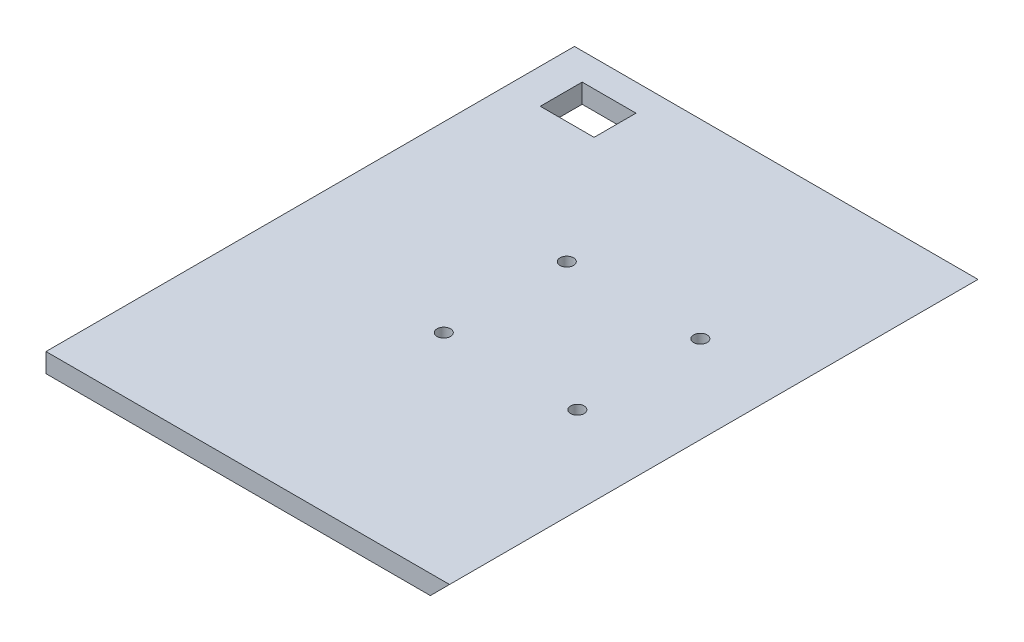
SolidWorks part; units mm, degrees
ref_plane "Ön Düzlem" through (0, 0, 0) normal (0, 0, 1) x (1, 0, 0)
ref_plane "Üst Düzlem" through (0, 0, 0) normal (0, 1, 0) x (1, 0, 0)
ref_plane "Sağ Düzlem" through (0, 0, 0) normal (1, 0, 0) x (0, 0, -1)
sketch "Çizim1" plane through (0, 0, 0) normal (1, 0, 0) x (0, 0, -1)
  line L0 (0, 0) -> (275, 0)
  line L1 (0, 10) -> (275, 10)
  line L2 (275, 10) -> (275, 0)
  line L3 (0, 10) -> (0, 0)
  dimension "D1" = 275
  dimension "D2" = 10
extrude "Yükseklik-Ekstrüzyon1" add sketch "Çizim1" along normal blind 200
sketch "Çizim2" plane through (200, 0, 0) normal (1, 0, 0) x (0, 0, -1)
  line L8 (0, 10) -> (0, 0)
  line L9 (0, 0) -> (275, 0)
  line L10 (275, 0) -> (275, 10)
  line L11 (275, 10) -> (0, 10)
  line L12 (0, 10) -> (0, 0)
  line L13 (0, 0) -> (275, 0)
  line L14 (275, 0) -> (275, 10)
  line L15 (275, 10) -> (0, 10)
  dimension "D1" = 0
extrude "Yükseklik-Ekstrüzyon2" add sketch "Çizim2" along normal blind 10
sketch "Çizim3" plane through (0, 0, -275) normal (0, 0, -1) x (-1, 0, 0)
  line L0 (-210, 10) -> (-200, 0)
  line L1 (-210, 10) -> (-210, 0)
  line L2 (-210, 0) -> (-200, 0)
extrude "Kes-Ekstrüzyon1" cut sketch "Çizim3" against normal through all
sketch "Sketch1" plane through (0, 10, 0) normal (0, 1, 0) x (1, 0, 0)
  circle A0 centre (95, 176.01) radius 3.5
  circle A1 centre (164.5, 176.01) radius 3.5
  circle A2 centre (95, 112.01) radius 3.5
  circle A3 centre (164.5, 112.01) radius 3.5
extrude "Cut-Extrude1" cut sketch "Sketch1" against normal up to next
sketch "Sketch2" plane through (0, 10, 0) normal (0, 1, 0) x (1, 0, 0)
  line L1 (18.0907, 260.9296) -> (46.0907, 260.9296)
  line L2 (18.0907, 260.9296) -> (18.0907, 239.1296)
  line L3 (18.0907, 239.1296) -> (46.0907, 239.1296)
  line L4 (46.0907, 260.9296) -> (46.0907, 239.1296)
extrude "Cut-Extrude2" cut sketch "Sketch2" against normal blind 10
